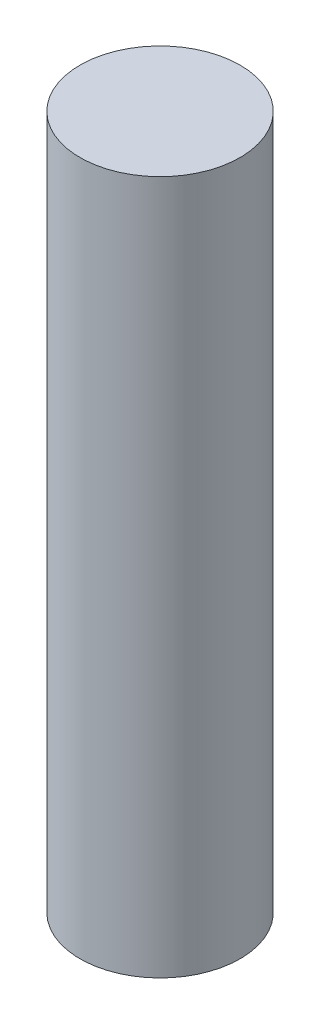
SolidWorks part; units mm, degrees
ref_plane "Front Plane" through (0, 0, 0) normal (0, 0, 1) x (1, 0, 0)
ref_plane "Top Plane" through (0, 0, 0) normal (0, 1, 0) x (1, 0, 0)
ref_plane "Right Plane" through (0, 0, 0) normal (1, 0, 0) x (0, 0, -1)
sketch "Sketch1" plane through (0, 0, 0) normal (0, 1, 0) x (1, 0, 0)
  circle A0 centre (0, 0) radius 1.5
extrude "Boss-Extrude1" add sketch "Sketch1" along normal blind 13
